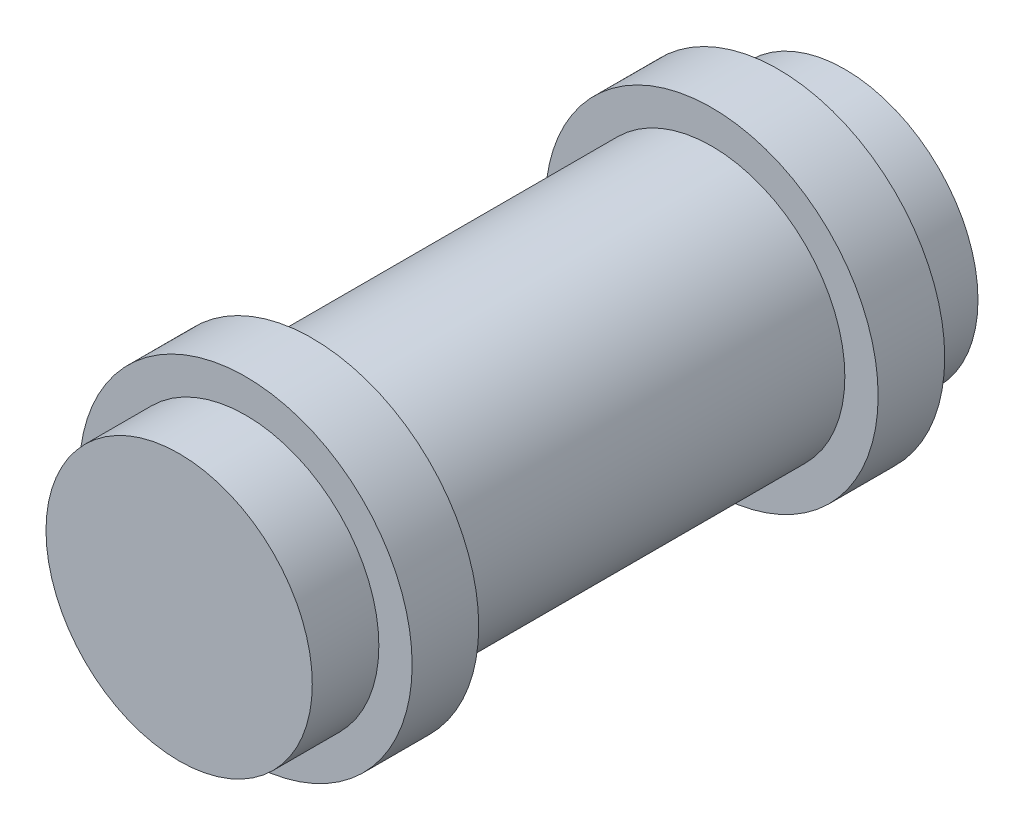
SolidWorks part; units mm, degrees
ref_plane "Front Plane" through (0, 0, 0) normal (0, 0, 1) x (1, 0, 0)
ref_plane "Top Plane" through (0, 0, 0) normal (0, 1, 0) x (1, 0, 0)
ref_plane "Right Plane" through (0, 0, 0) normal (1, 0, 0) x (0, 0, -1)
sketch "Sketch1" plane through (0, 0, 0) normal (0, 0, 1) x (1, 0, 0)
  circle A0 centre (0, 0) radius 10
  dimension "D1" = 20
extrude "Boss-Extrude1" add sketch "Sketch1" along normal blind 50
sketch "Sketch2" plane through (0, 0, 50) normal (0, 0, 1) x (1, 0, 0)
  circle A0 centre (0, 0) radius 12.5
  dimension "D1" = 25
extrude "Boss-Extrude2" add sketch "Sketch2" against normal blind 5 from offset 5 offset against normal yes
ref_plane "Plane1" through (0, 0, 25) normal (0, 0, 1) x (1, 0, 0)
mirror "Mirror1" about plane through (0, 0, 25) normal (0, 0, 1) of "Boss-Extrude2"
